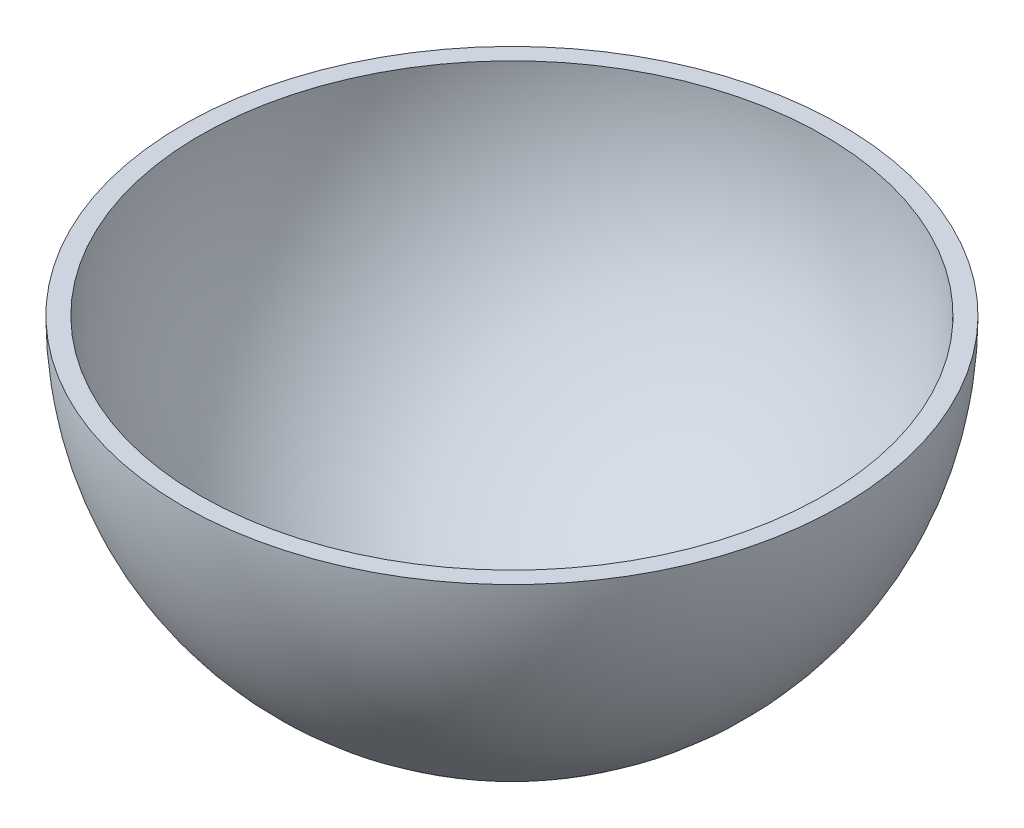
SolidWorks part; units mm, degrees
ref_plane "Alzado" through (0, 0, 0) normal (0, 0, 1) x (1, 0, 0)
ref_plane "Planta" through (0, 0, 0) normal (0, 1, 0) x (1, 0, 0)
ref_plane "Vista lateral" through (0, 0, 0) normal (1, 0, 0) x (0, 0, -1)
sketch "Croquis1" plane through (0, 0, 0) normal (1, 0, 0) x (0, 0, -1)
  line L0 (0, 29) -> (0, -28) construction
  line L1 (-0.5, 27.9955) -> (-0.5, 26.4953)
  line L2 (-19.1511, 16.0697) -> (0, 0) construction
  line L3 (-19.1511, 16.0697) -> (-20.3002, 17.0339)
  line L4 (-0.5, 26.4953) -> (-0.5, 24.995)
  line L5 (0, -26.5) -> (0, -28)
  arc A0 (-0.5, 27.9955) -> (0, -28) centre (0, 0) ccw
  arc A1 (-20.3002, 17.0339) -> (0, -26.5) centre (0, 0) ccw
  arc A2 (-19.1511, 16.0697) -> (-0.5, 24.995) centre (0, 0) cw
  arc A3 (-0.5, 26.4953) -> (-20.3002, 17.0339) centre (0, 0) ccw construction
  dimension "D1" = 56
  dimension "D2" = 53
  dimension "D5" = 1.5
  dimension "D3" = 0.5
  dimension "D4" = 50
revolve "Revolución3" add sketch "Croquis1" angle 360 about L0
sketch "Croquis2" plane through (0, 0, 0) normal (1, 0, 0) x (0, 0, -1)
  line L0 (0, 0) -> (0, 42.1069) construction
  line L1 (0, 30) -> (0, 16)
  line L2 (-10, 16) -> (0, 16)
  line L3 (-10, 16) -> (-10, 30)
  line L4 (-10, 30) -> (0, 30)
  line L5 (10, 16) -> (10, 30) construction
  line L6 (-10, 16) -> (10, 30) construction
  line L7 (-10, 30) -> (10, 16) construction
  line L8 (0, 30) -> (10, 30) construction
  line L9 (0, 16) -> (10, 16) construction
  point P3 (0, 23)
  dimension "D1" = 20
  dimension "D2" = 14
  dimension "D3" = 23
revolve "Cortar-Revolución2" cut sketch "Croquis2" angle 360 about L0
fillet "Redondeo1" radius 1 3 edges at (0, 26.1534, -10) (0, 16.0697, 19.1511) (0, 22.9129, -10)
sketch "Croquis3" plane through (0, 0, 0) normal (0, 1, 0) x (1, 0, 0)
  circle A0 centre (0, 0) radius 29.8457
extrude "Cortar-Extruir1" cut sketch "Croquis3" along normal blind 30
ref_plane "Plano1" through (0, -28, 0) normal (0, -1, 0) x (-1, 0, 0)
sketch "Croquis4" plane through (0, -28, 0) normal (0, -1, 0) x (-1, 0, 0)
  circle A0 centre (0, 0) radius 7.5
  circle A1 centre (0, 0) radius 10
  circle A2 centre (0, 0) radius 12.5
  circle A3 centre (0, 0) radius 15
  circle A4 centre (0, 0) radius 17.5
  circle A5 centre (0, 0) radius 20
  circle A6 centre (0, 0) radius 22.5
  circle A7 centre (0, 0) radius 24
  circle A8 centre (0, 0) radius 26.5
  dimension "D1" = 15
  dimension "D2" = 20
  dimension "D3" = 25
  dimension "D4" = 30
  dimension "D5" = 35
  dimension "D6" = 40
  dimension "D7" = 45
  dimension "D8" = 48
  dimension "D9" = 53
extrude "Extruir-Lámina1" [suppressed] add sketch "Croquis4" against normal up to surface (1.0939 mm away) thin contours A0 | A1 | A2 | A3 | A4 | A5 | A6 | A7 | A8
